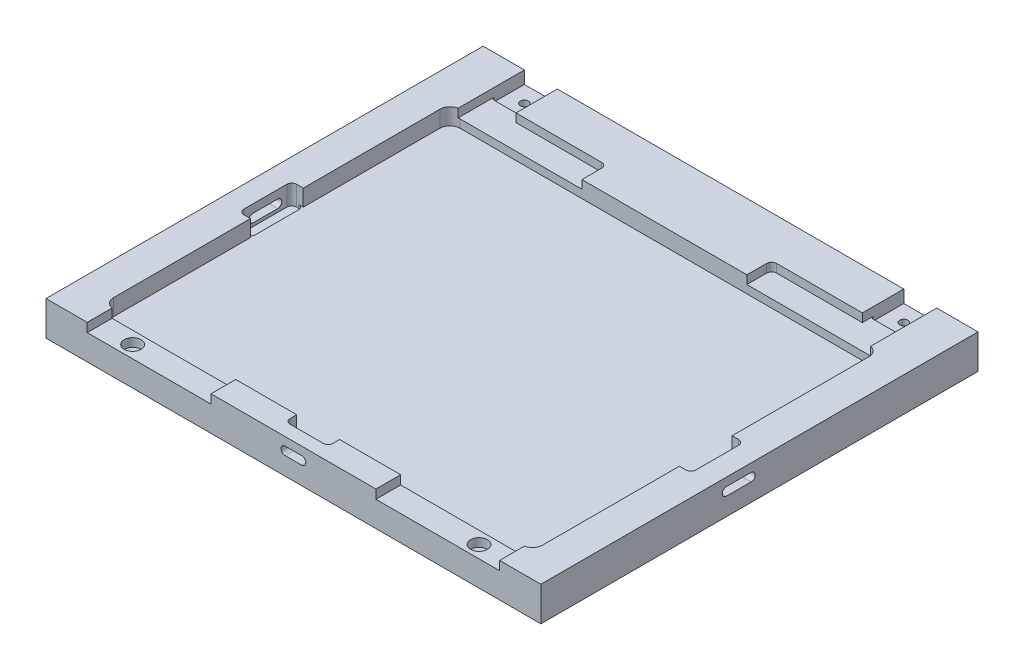
SolidWorks part; units mm, degrees
material "PA Тип 6"
ref_plane "Front" through (0, 0, 0) normal (0, 0, 1) x (1, 0, 0)
ref_plane "Top" through (0, 0, 0) normal (0, 1, 0) x (1, 0, 0)
ref_plane "Right" through (0, 0, 0) normal (1, 0, 0) x (0, 0, -1)
sketch "Эскиз1" plane through (0, 0, 0) normal (0, 1, 0) x (1, 0, 0)
  line L1 (-130, 132.5) -> (130, 132.5)
  line L2 (-130, 132.5) -> (-130, -132.5)
  line L3 (-130, -132.5) -> (130, -132.5)
  line L4 (130, 132.5) -> (130, -132.5)
  line L5 (-130, 132.5) -> (130, -132.5) construction
  line L6 (-130, -132.5) -> (130, 132.5) construction
  point P0 (0, 0)
  dimension "D1" = 260
  dimension "D2" = 265
extrude "База" add sketch "Эскиз1" along normal blind 5.8
sketch "Эскиз17" plane through (0, 5.8, 0) normal (0, 1, 0) x (1, 0, 0)
  line L0 (130, -132.5) -> (130, 132.5) construction
  line L1 (-130, -132.5) -> (130, -132.5)
  line L2 (-130, -132.5) -> (-130, -117.5)
  line L3 (-130, -117.5) -> (130, -117.5)
  line L4 (130, -132.5) -> (130, -117.5)
  dimension "D1" = 15
extrude "Стенка спереди" add sketch "Эскиз17" along normal blind 10
sketch "Эскиз19" plane through (130, 0, 0) normal (1, 0, 0) x (0, 0, -1)
  line L1 (-132.5, 15.8) -> (132.5, 15.8)
  line L2 (-132.5, 15.8) -> (-132.5, 0)
  line L3 (-132.5, 0) -> (132.5, 0)
  line L4 (132.5, 15.8) -> (132.5, 0)
extrude "Стенка справа" add sketch "Эскиз19" along normal blind 20
sketch "Эскиз20" plane through (-130, 0, 0) normal (-1, 0, 0) x (0, 0, 1)
  line L1 (132.5, 15.8) -> (-132.5, 15.8)
  line L2 (132.5, 15.8) -> (132.5, 0)
  line L3 (132.5, 0) -> (-132.5, 0)
  line L4 (-132.5, 15.8) -> (-132.5, 0)
extrude "Стенка слева" add sketch "Эскиз20" along normal blind 20
sketch "Эскиз22" plane through (0, 15.8, 0) normal (0, 1, 0) x (1, 0, 0)
  line L0 (130, -117.5) -> (-130, -117.5) construction
  line L1 (-125, -117.5) -> (-50, -117.5)
  line L2 (-125, -117.5) -> (-125, -132.5)
  line L3 (-125, -132.5) -> (-50, -132.5)
  line L4 (-50, -117.5) -> (-50, -132.5)
  line L5 (-150, -132.5) -> (150, -132.5) construction
  line L6 (130, -117.5) -> (-130, -117.5) construction
  line L7 (50, -117.5) -> (125, -117.5)
  line L8 (50, -117.5) -> (50, -132.5)
  line L9 (50, -132.5) -> (125, -132.5)
  line L10 (125, -117.5) -> (125, -132.5)
  line L11 (-50, -125) -> (0, -125) construction
  line L12 (0, -125) -> (50, -125) construction
  dimension "D1" = 250
  dimension "D2" = 100
extrude "Вырез свободной стороны" cut sketch "Эскиз22" against normal blind 5.4
sketch "Эскиз25" plane through (0, 5.8, 0) normal (0, 1, 0) x (1, 0, 0)
  line L0 (125, 132.5) -> (125, 92.4)
  line L1 (130, 132.5) -> (-130, 132.5) construction
  line L2 (125, 92.4) -> (130, 92.4)
  line L3 (130, -117.5) -> (130, 132.5) construction
  line L5 (130, 132.5) -> (125, 132.5)
  line L7 (-130, 92.4) -> (-125, 92.4)
  line L8 (-130, -117.5) -> (-130, 132.5) construction
  line L9 (-125, 92.4) -> (-125, 132.5)
  line L10 (130, 132.5) -> (-130, 132.5) construction
  line L11 (-125, 132.5) -> (-130, 132.5)
  line L12 (-130, 132.5) -> (-130, 92.4)
  line L13 (-125, -117.5) -> (-125, -132.5) construction
  line L14 (130, 132.5) -> (130, 92.4)
  line L15 (125, -132.5) -> (125, -117.5) construction
  dimension "D1" = 40.1
extrude "НапрявляющийВынос-1" add sketch "Эскиз25" along normal blind 10
sketch "Эскиз26" plane through (0, 5.8, 0) normal (0, 1, 0) x (1, 0, 0)
  line L0 (125, 132.5) -> (125, 92.4) construction
  line L1 (-125, 132.5) -> (125, 132.5)
  line L2 (-125, 132.5) -> (-125, 107.4)
  line L3 (-125, 107.4) -> (125, 107.4)
  line L4 (125, 132.5) -> (125, 107.4)
  dimension "D1" = 25.1
extrude "Бобышка-Вытянуть1" add sketch "Эскиз26" along normal blind 4.9
hole_wizard "Крепление для уровня M6" positions "Эскиз15" profile "Эскиз16" tap size "M6" standard "DIN" end condition through all
sketch "Эскиз15" plane through (0, 10.7, 0) normal (0, 1, 0) x (1, 0, 0)
  line L1 (-115, 122.5) -> (0, 122.5) construction
  line L2 (0, 122.5) -> (115, 122.5) construction
  line L7 (125, 132.5) -> (-125, 132.5) construction
  point P0 (-115, 122.5)
  point P2 (115, 122.5)
  dimension "D1" = 230
  dimension "D2" = 10
cosmetic thread "Отверстие резьбы3" parameters "D2"=6
cosmetic thread "Отверстие резьбы4" parameters "D2"=6
sketch "Эскиз16" plane through (-115, 10.7, -122.5) normal (1, 0, 0) x (0, 0, 1)
  line L0 (0, 0) -> (0, 10.7)
  line L1 (0, 10.7) -> (2.5, 10.7)
  line L2 (2.5, 10.7) -> (2.5, 0.525)
  line L3 (2.5, 0.525) -> (3.025, 0)
  line L5 (3.025, 0) -> (0, 0)
  line L6 (-2.5, 0.525) -> (-3.025, 0) construction
  line L11 (0, -6.35) -> (0, 107.95) construction
  dimension "Диаметр проходного сверла" = 5
  dimension "Глубина проходного сверла" = 10.7
  dimension "Диаметр передней зенковки" = 6.05
  dimension "Угол передней зенковки" = 90
sketch "Эскиз27" plane through (0, 10.7, 0) normal (0, 1, 0) x (1, 0, 0)
  line L0 (125, 132.5) -> (-125, 132.5) construction
  line L1 (-105, 132.5) -> (105, 132.5)
  line L2 (-105, 132.5) -> (-105, 107.4)
  line L3 (-105, 107.4) -> (105, 107.4)
  line L4 (105, 132.5) -> (105, 107.4)
  line L5 (-125, 107.4) -> (125, 107.4) construction
  point P8 (0, 107.4)
  dimension "D1" = 210
extrude "РеброЖесткости" add sketch "Эскиз27" along normal up to surface (5.1 mm away) up to face at (-132.5, 15.8, 6.275)
sketch "Эскиз28" plane through (150, 0, 0) normal (1, 0, 0) x (0, 0, -1)
  line L0 (-20.05, 8.3) -> (-5.05, 8.3) construction
  line L1 (-20.05, 10.8) -> (-5.05, 10.8)
  line L2 (-20.05, 5.8) -> (-5.05, 5.8)
  line L3 (-132.5, 0) -> (132.5, 0) construction
  line L5 (-117.5, 5.8) -> (92.4, 5.8) construction
  arc A0 (-20.05, 10.8) -> (-20.05, 5.8) centre (-20.05, 8.3) ccw
  arc A1 (-5.05, 5.8) -> (-5.05, 10.8) centre (-5.05, 8.3) ccw
  point P2 (-12.55, 8.3)
  point P17 (-12.55, 5.8)
  dimension "D2" = 2.5
  dimension "D1" = 15
  dimension "D3" = 8.3
extrude "Регулировка-1" cut sketch "Эскиз28" against normal through all
sketch "Эскиз37" plane through (0, 0, 132.5) normal (0, 0, 1) x (1, 0, 0)
  line L0 (-5, 8.3) -> (5, 8.3) construction
  line L1 (-5, 10.8) -> (5, 10.8)
  line L2 (-5, 5.8) -> (5, 5.8)
  line L3 (-150, 0) -> (150, 0) construction
  arc A0 (-5, 10.8) -> (-5, 5.8) centre (-5, 8.3) ccw
  arc A1 (5, 5.8) -> (5, 10.8) centre (5, 8.3) ccw
  point P2 (0, 8.3)
  dimension "D2" = 2.5
  dimension "D1" = 8.3
  dimension "D3" = 10
extrude "Регулировка-2" cut sketch "Эскиз37" against normal up to next
sketch "Эскиз29" plane through (0, 10.4, 0) normal (0, 1, 0) x (1, 0, 0)
  line L0 (-125, -117.5) -> (-125, -132.5) construction
  line L2 (-105, -125) -> (105, -125) construction
  circle A0 centre (-105, -125) radius 5.1
  circle A1 centre (105, -125) radius 5.1
  point P4 (0, -125)
  point P7 (-125, -125)
  dimension "D1" = 10.2
  dimension "D2" = 210
extrude "Магниты" cut sketch "Эскиз29" against normal blind 5.1
hole_wizard "КреплениеМагнитов-М3" positions "Эскиз30" profile "Эскиз31" tap size "M3" standard "DIN" end condition through all
sketch "Эскиз30" plane through (0, 5.3, 0) normal (0, 1, 0) x (1, 0, 0)
  point P0 (-105, -125)
  point P3 (105, -125)
sketch "Эскиз31" plane through (-105, 5.3, 125) normal (1, 0, 0) x (0, 0, 1)
  line L0 (0, 0) -> (0, 5.3)
  line L1 (0, 5.3) -> (1.25, 5.3)
  line L2 (1.25, 5.3) -> (1.25, 0.275)
  line L3 (1.25, 0.275) -> (1.525, 0)
  line L5 (1.525, 0) -> (0, 0)
  line L6 (-1.25, 0.275) -> (-1.525, 0) construction
  line L11 (0, -6.35) -> (0, 107.95) construction
  dimension "Диаметр проходного сверла" = 2.5
  dimension "Глубина проходного сверла" = 5.3
  dimension "Диаметр передней зенковки" = 3.05
  dimension "Угол передней зенковки" = 90
cosmetic thread "Отверстие резьбы5" parameters "D2"=3
cosmetic thread "Отверстие резьбы6" parameters "D2"=3
sketch "Эскиз32" plane through (0, 5.8, 0) normal (0, 1, 0) x (1, 0, 0)
  line L1 (-125, 107.4) -> (125, 107.4)
  line L2 (-125, 107.4) -> (-125, 92.4)
  line L3 (-125, 92.4) -> (125, 92.4)
  line L4 (125, 107.4) -> (125, 92.4)
extrude "Бобышка-Вытянуть3" add sketch "Эскиз32" along normal up to surface (4.9 mm away) up to face at (-115, 10.7, -119.475)
sketch "Эскиз38" plane through (0, 10.7, 0) normal (0, 1, 0) x (1, 0, 0)
  line L0 (105, 107.4) -> (-105, 107.4) construction
  line L1 (-50, 107.4) -> (50, 107.4)
  line L2 (-50, 107.4) -> (-50, 92.4)
  line L3 (-50, 92.4) -> (50, 92.4)
  line L4 (50, 107.4) -> (50, 92.4)
  line L5 (-125, 92.4) -> (125, 92.4) construction
  point P8 (0, 92.4)
  dimension "D1" = 100
extrude "НаправляющийВынос-2" add sketch "Эскиз38" along normal up to surface (5.1 mm away) up to face at (0, 15.8, -119.95)
sketch "Эскиз34" plane through (0, 0, 0) normal (0, -1, 0) x (1, 0, 0)
  line L1 (150, -132.5) -> (-150, -132.5)
  line L2 (150, -132.5) -> (150, 132.5)
  line L3 (150, 132.5) -> (-150, 132.5)
  line L4 (-150, -132.5) -> (-150, 132.5)
  line L5 (150, -132.5) -> (-150, 132.5) construction
  line L6 (150, 132.5) -> (-150, -132.5) construction
  point P0 (0, 0)
extrude "Бобышка-Вытянуть4" add sketch "Эскиз34" along normal blind 5
sketch "Эскиз33" plane through (0, -5, 0) normal (0, -1, 0) x (1, 0, 0)
  line L0 (-150, 132.5) -> (-150, -132.5) construction
  line L23 (150, -132.5) -> (150, 132.5) construction
  line L24 (150, 132.5) -> (-150, 132.5) construction
  line L25 (-150, -132.5) -> (150, -132.5) construction
  circle A0 centre (0, 0) radius 20
  circle A1 centre (-120, 102.5) radius 20
  circle A2 centre (120, 102.5) radius 20
  circle A3 centre (120, -92.5) radius 20
  circle A4 centre (-120, -92.5) radius 20
  dimension "D1" = 40
  dimension "D2" = 30
  dimension "D3" = 30
  dimension "D4" = 30
  dimension "D5" = 40
extrude "Ножки" add sketch "Эскиз33" along normal blind 5.2
sketch "Эскиз36" plane through (0, 15.8, 0) normal (0, 1, 0) x (1, 0, 0)
  line L0 (130, -117.5) -> (130, -20.05) construction
  line L1 (137, -28.55) -> (130, -28.55)
  line L2 (137, -28.55) -> (137, 3.45)
  line L3 (137, 3.45) -> (130, 3.45)
  line L4 (130, -28.55) -> (130, 3.45)
  line L6 (130, 92.4) -> (130, -117.5) construction
  line L7 (-130, 92.4) -> (-130, -5.05) construction
  line L8 (-130, 3.45) -> (-137, 3.45)
  line L9 (-130, 3.45) -> (-130, -28.55)
  line L10 (-130, -28.55) -> (-137, -28.55)
  line L11 (-137, 3.45) -> (-137, -28.55)
  line L12 (-5, -117.5) -> (-130, -117.5) construction
  line L13 (-13, -117.5) -> (13, -117.5)
  line L14 (-13, -117.5) -> (-13, -124.5)
  line L15 (-13, -124.5) -> (13, -124.5)
  line L16 (13, -117.5) -> (13, -124.5)
  point P8 (130, -12.55)
  point P9 (130, -12.55)
  point P22 (0, -117.5)
  dimension "D1" = 7
  dimension "D2" = 32
  dimension "D3" = 26
extrude "КонтрГайка" cut sketch "Эскиз36" against normal blind 12
fillet "Скругление2" radius 3 14 edges at (130, 4.8, -3.45) (137, 9.8, -3.45) (137, 9.8, 28.55) (130, 4.8, 28.55) (-137, 9.8, 28.55) (-130, 4.8, 28.55) (-130, 4.8, -3.45) (-137, 9.8, -3.45) (-50, 13.25, -107.4) (50, 13.25, -107.4) (-13, 9.8, 124.5) (13, 9.8, 124.5) (13, 4.8, 117.5) (-13, 4.8, 117.5)
fillet "Скругление3" radius 6 4 edges at (130, 10.8, 117.5) (130, 10.8, -92.4) (-130, 10.8, 117.5) (-130, 10.8, -92.4)
sketch "Эскиз39" plane through (0, 10.7, 0) normal (0, 1, 0) x (1, 0, 0)
  line L1 (-125, 112.5) -> (-105, 112.5)
  line L2 (-125, 112.5) -> (-125, 132.5)
  line L3 (-125, 132.5) -> (-105, 132.5)
  line L4 (-105, 112.5) -> (-105, 132.5)
  line L5 (-125, 112.5) -> (-105, 132.5) construction
  line L6 (-125, 132.5) -> (-105, 112.5) construction
  line L7 (125, 112.5) -> (105, 112.5)
  line L8 (125, 112.5) -> (125, 132.5)
  line L9 (125, 132.5) -> (105, 132.5)
  line L10 (105, 112.5) -> (105, 132.5)
  line L11 (125, 112.5) -> (105, 132.5) construction
  line L12 (125, 132.5) -> (105, 112.5) construction
  point P0 (-115, 122.5)
  point P7 (115, 122.5)
extrude "Вырез-Вытянуть1" cut sketch "Эскиз39" against normal blind 2.5
fillet "Скругление4" radius 1.5 4 edges at (105, 9.45, -112.5) (125, 9.45, -112.5) (-105, 9.45, -112.5) (-125, 9.45, -112.5)
